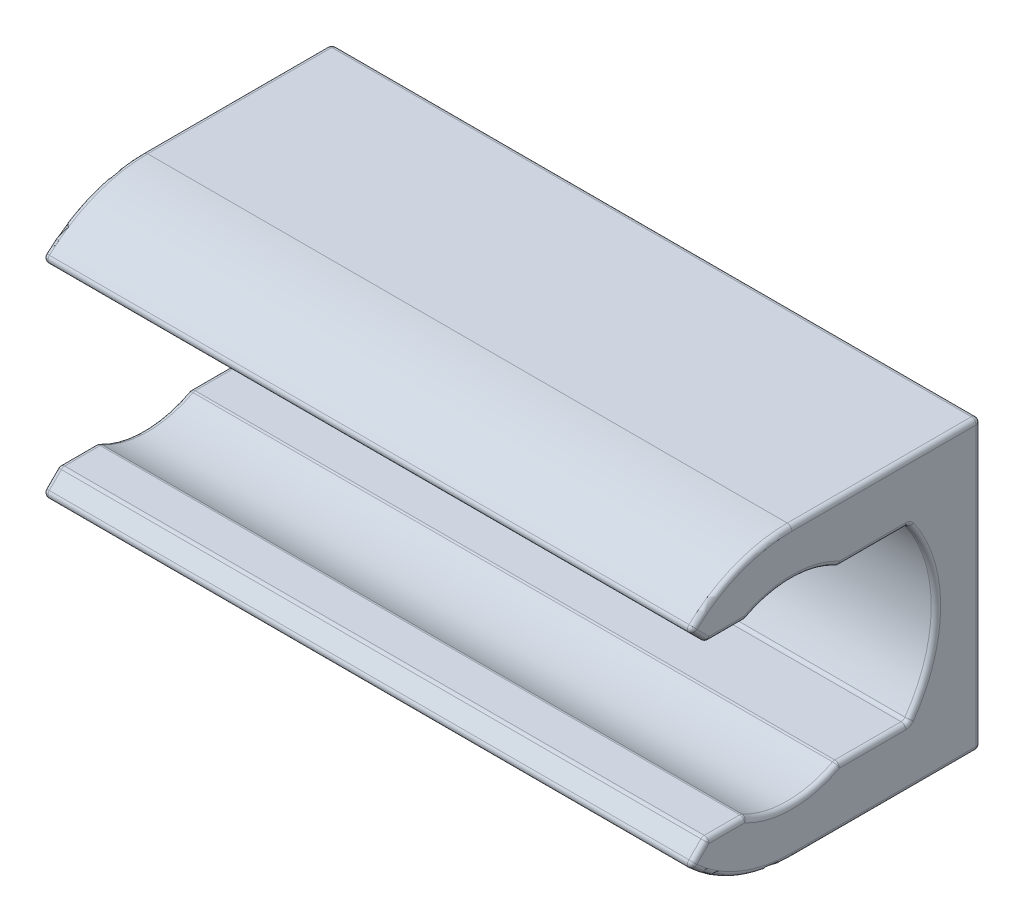
SolidWorks part; units mm, degrees
ref_plane "Front Plane" through (0, 0, 0) normal (0, 0, 1) x (1, 0, 0)
ref_plane "Top Plane" through (0, 0, 0) normal (0, 1, 0) x (1, 0, 0)
ref_plane "Right Plane" through (0, 0, 0) normal (1, 0, 0) x (0, 0, -1)
sketch "Sketch1" plane through (0, 0, 0) normal (1, 0, 0) x (0, 0, -1)
  line L0 (0, 0) -> (-4.3134, 4.3134)
  line L1 (-4.3134, 4.3134) -> (-4.3134, -4.3134)
  line L2 (-4.3134, -4.3134) -> (0, 0)
  line L3 (4.3134, 4.3134) -> (8, 4.3134)
  line L4 (8, 4.3134) -> (8, -4.3134)
  line L5 (8, -4.3134) -> (4.3134, -4.3134)
  line L6 (-8, 3.6) -> (8, 3.6)
  line L7 (-8, -6.1) -> (8, -6.1)
  line L8 (-8, -6.1) -> (-8, 6.1)
  line L9 (-8, 6.1) -> (8, 6.1)
  line L10 (8, -6.1) -> (8, 6.1)
  line L11 (-8, -6.1) -> (8, 6.1) construction
  line L12 (-8, 6.1) -> (8, -6.1) construction
  line L13 (8, -3.6) -> (-8, -3.6)
  circle A0 centre (0, 0) radius 4.1
  circle A1 centre (0, 0) radius 6.1
  dimension "D1" = 8.2
  dimension "D3" = 90
  dimension "D4" = 8
  dimension "D5" = 2.5
  dimension "D6" = 2.5
  dimension "D2" = 2
extrude "Boss-Extrude1" add sketch "Sketch1" along normal blind 27.5 contours L6 A1 L0 A0 | A1 L3 L10 L9 | A1 L6 L4 L3 | A1 L13 L4 L6 | A1 L7 L10 L5 | A1 L5 L10 L13 | L2 A1 L13 A0
fillet "Fillet1" radius 0.2 40 edges at (13.75, 4.3134, 4.3134) (13.75, -4.3134, 4.3134) (13.75, 6.1, -8) (13.75, 3.6, 3.6) (13.75, 3.6, -1.9621) (13.75, 3.6, 1.9621) (13.75, 3.6, -4.9244) (13.75, -3.6, -4.9244) (13.75, -3.6, 1.9621) (13.75, -3.6, -1.9621) (13.75, -3.6, 3.6) (13.75, -6.1, -8) (0, -6.1, -4) (27.5, -6.1, -4) (27.5, -5.6357, 2.3344) (0, -5.6357, 2.3344) (0, -3.9567, 3.9567) (27.5, -3.9567, 3.9567) (27.5, -3.6, 2.7811) (0, -3.6, 2.7811) (0, -4.1, 0) (27.5, -4.1, 0) (27.5, -3.6, -3.4433) (0, -3.6, -3.4433) (27.5, 0, -6.1) (0, 0, -6.1) (27.5, 3.6, -3.4433) (0, 3.6, -3.4433) (0, 4.1, 0) (27.5, 4.1, 0) (27.5, 3.6, 2.7811) (0, 3.6, 2.7811) (0, 3.9567, 3.9567) (27.5, 3.9567, 3.9567) (27.5, 5.6357, 2.3344) (0, 5.6357, 2.3344) (0, 6.1, -4) (27.5, 6.1, -4) (0, 0, -8) (27.5, 0, -8)
